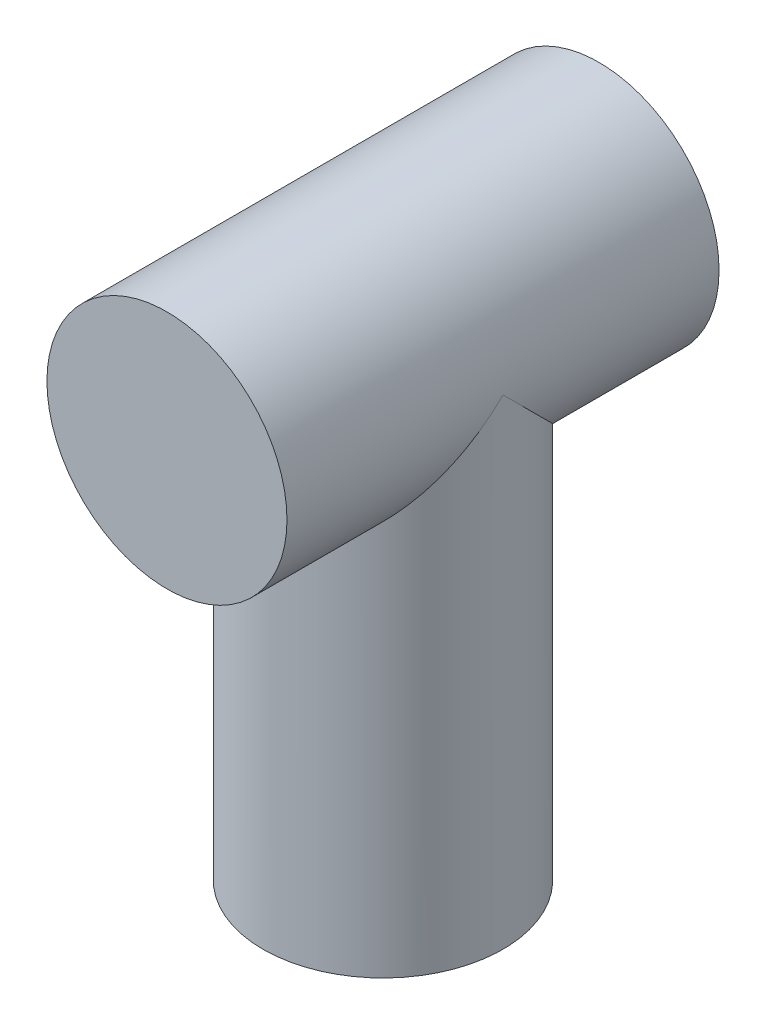
SolidWorks part; units mm, degrees
ref_plane "Front Plane" through (0, 0, 0) normal (0, 0, 1) x (1, 0, 0)
ref_plane "Top Plane" through (0, 0, 0) normal (0, 1, 0) x (1, 0, 0)
ref_plane "Right Plane" through (0, 0, 0) normal (1, 0, 0) x (0, 0, -1)
sketch "Sketch1" plane through (0, 0, 0) normal (0, 0, 1) x (1, 0, 0)
  circle A0 centre (0, 0) radius 12.5
  dimension "D1" = 25
extrude "Boss-Extrude1" add sketch "Sketch1" along normal mid plane 45
sketch "Sketch2" plane through (0, 0, 0) normal (0, 1, 0) x (1, 0, 0)
  line L0 (12.5, -22.5) -> (12.5, 22.5) construction
  line L1 (-12.5, -12.5) -> (12.5, -12.5)
  line L2 (-12.5, -12.5) -> (-12.5, 12.5)
  line L3 (-12.5, 12.5) -> (12.5, 12.5)
  line L4 (12.5, -12.5) -> (12.5, 12.5)
  line L5 (-12.5, -12.5) -> (12.5, 12.5) construction
  line L6 (-12.5, 12.5) -> (12.5, -12.5) construction
  circle A0 centre (0, 0) radius 12.5
  point P0 (0, 0)
  dimension "D1" = 25
extrude "Boss-Extrude2" add sketch "Sketch2" against normal blind 50 contours A0
